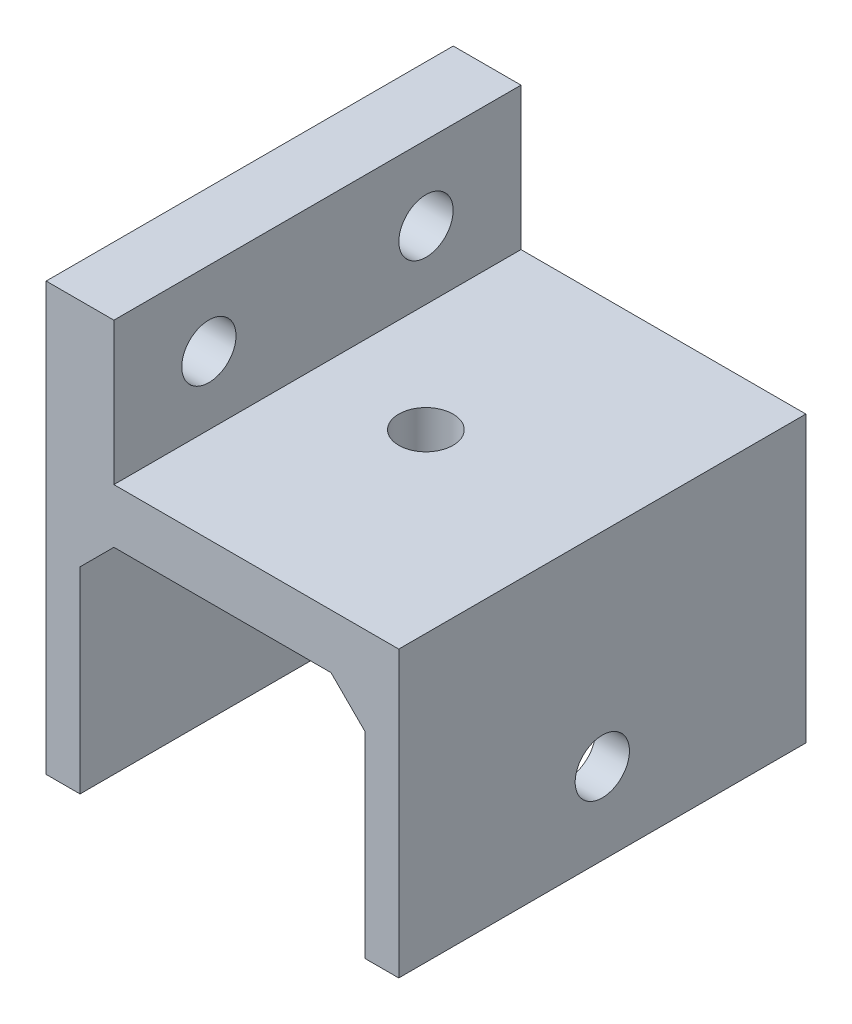
SolidWorks part; units mm, degrees
ref_plane "Front Plane" through (0, 0, 0) normal (0, 0, 1) x (1, 0, 0)
ref_plane "Top Plane" through (0, 0, 0) normal (0, 1, 0) x (1, 0, 0)
ref_plane "Right Plane" through (0, 0, 0) normal (1, 0, 0) x (0, 0, -1)
sketch "Model" plane through (0, 0, 0) normal (0, 0, 1) x (1, 0, 0)
  line L11 (112.7453, 60.3854) -> (112.7453, 93.7102)
  line L12 (108.7829, 60.3854) -> (112.7453, 60.3854)
  line L13 (108.7829, 83.3978) -> (108.7829, 60.3854)
  line L14 (104.8205, 87.3602) -> (108.7829, 83.3978)
  line L15 (79.4205, 87.3602) -> (104.8205, 87.3602)
  line L16 (75.4581, 83.3978) -> (79.4205, 87.3602)
  line L17 (75.4581, 60.3854) -> (75.4581, 83.3978)
  line L18 (71.4957, 60.3854) -> (75.4581, 60.3854)
  line L19 (71.4957, 110.3726) -> (71.4957, 60.3854)
  line L20 (112.7453, 93.7102) -> (79.4205, 93.7102)
  line L21 (79.4205, 110.3726) -> (71.4957, 110.3726)
  line L22 (79.4205, 93.7102) -> (79.4205, 110.3726)
extrude "Boss-Extrude2" add sketch "Model" along normal blind 47.625
sketch "Sketch2" plane through (0, 93.7102, 0) normal (0, 1, 0) x (1, 0, 0)
  line L0 (112.7453, -23.8125) -> (79.4205, -23.8125) construction
  line L1 (112.7453, -47.625) -> (112.7453, 0) construction
  line L2 (79.4205, -47.625) -> (79.4205, 0) construction
  circle A0 centre (92.1078, -23.8125) radius 3.175
  dimension "D1" = 20.6375
  dimension "D2" = 6.35
extrude "Cut-Extrude1" cut sketch "Sketch2" against normal through all
sketch "Sketch4" plane through (71.4957, 0, 0) normal (-1, 0, 0) x (0, 0, 1)
  line L0 (0, 101.6604) -> (47.625, 101.6604) construction
  line L1 (0, 110.3726) -> (0, 60.3854) construction
  line L2 (47.625, 110.3726) -> (47.625, 60.3854) construction
  line L3 (47.625, 60.3854) -> (0, 60.3854) construction
  circle A0 centre (11.1125, 101.6604) radius 3.175
  circle A1 centre (36.5125, 101.6604) radius 3.175
  dimension "D1" = 6.35
  dimension "D2" = 6.35
  dimension "D3" = 11.1125
  dimension "D4" = 11.1125
  dimension "D5" = 41.275
extrude "Cut-Extrude2" cut sketch "Sketch4" against normal through all
sketch "Sketch5" plane through (112.7453, 0, 0) normal (1, 0, 0) x (0, 0, -1)
  line L0 (-23.8125, 60.3854) -> (-23.8125, 93.7102) construction
  line L1 (-47.625, 60.3854) -> (0, 60.3854) construction
  line L2 (-47.625, 93.7102) -> (0, 93.7102) construction
  circle A0 centre (-23.8125, 69.9104) radius 3.175
  dimension "D1" = 9.525
  dimension "D2" = 6.35
extrude "Cut-Extrude3" cut sketch "Sketch5" against normal blind 47.625
